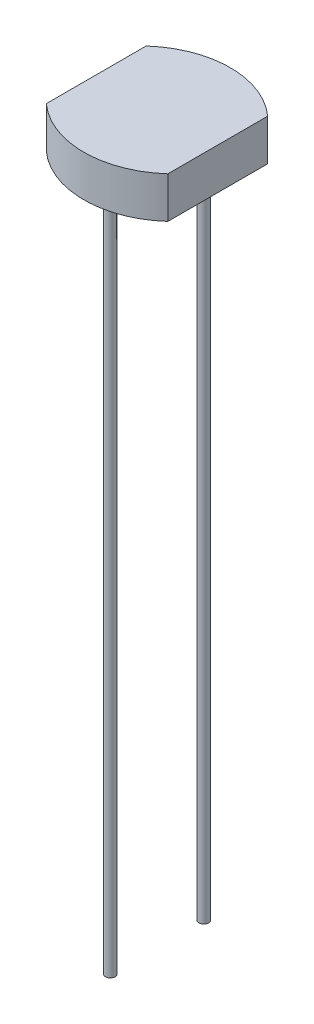
SolidWorks part; units mm, degrees
ref_plane "Front Plane" through (0, 0, 0) normal (0, 0, 1) x (1, 0, 0)
ref_plane "Top Plane" through (0, 0, 0) normal (0, 1, 0) x (1, 0, 0)
ref_plane "Right Plane" through (0, 0, 0) normal (1, 0, 0) x (0, 0, -1)
sketch "Sketch1" plane through (0, 0, 0) normal (0, 1, 0) x (1, 0, 0)
  line L0 (0, 3.375) -> (0, -3.375) construction
  line L1 (-2.8, -3.375) -> (2.8, -3.375)
  line L2 (-2.8, -3.375) -> (-2.8, 3.375)
  line L3 (-2.8, 3.375) -> (2.8, 3.375)
  line L4 (2.8, -3.375) -> (2.8, 3.375)
  line L5 (-2.8, -3.375) -> (2.8, 3.375) construction
  line L6 (-2.8, 3.375) -> (2.8, -3.375) construction
  line L7 (-2.8, 0) -> (2.8, 0)
  circle A0 centre (0, -0.8059) radius 4.1809
  point P0 (0, 0)
  dimension "D1" = 5.6
  dimension "D2" = 6.75
extrude "Boss-Extrude1" add sketch "Sketch1" along normal blind 1.9 contours L4 A0 L2 L7
ref_plane "Plane1" through (0, 0, 0) normal (0, 0, 1) x (1, 0, 0)
sketch "Sketch2" plane through (0, 0, 0) normal (0, -1, 0) x (1, 0, 0)
  line L0 (0, -3.375) -> (0, 0) construction
  line L1 (0, -2.375) -> (0.6053, -2.375) construction
  arc A0 (-2.8, -2.2989) -> (2.8, -2.2989) centre (0, 0.8059) ccw construction
  circle A1 centre (0, -2.15) radius 0.225
  dimension "D1" = 0.45
  dimension "D2" = 1
extrude "Boss-Extrude2" add sketch "Sketch2" along normal blind 31.5
mirror "Mirror2" about plane through (0, 0, 0) normal (0, 0, 1) of "Boss-Extrude2", "Boss-Extrude1"
sketch "Sketch3" plane through (0, 1.9, 0) normal (0, 1, 0) x (1, 0, 0)
  line L2 (2.8, -2.2989) -> (2.8, 2.2989)
  line L3 (-2.8, 2.2989) -> (-2.8, -2.2989)
  line L4 (2.8, -2.2989) -> (2.8, 2.2989)
  line L5 (-2.8, 2.2989) -> (-2.8, -2.2989)
  arc A2 (2.8, 2.2989) -> (-2.8, 2.2989) centre (0, -0.8059) ccw
  arc A3 (-2.8, -2.2989) -> (2.8, -2.2989) centre (0, 0.8059) ccw
  arc A4 (2.8, 2.2989) -> (-2.8, 2.2989) centre (0, -0.8059) ccw
  arc A5 (-2.8, -2.2989) -> (2.8, -2.2989) centre (0, 0.8059) ccw
  dimension "D1" = 0
